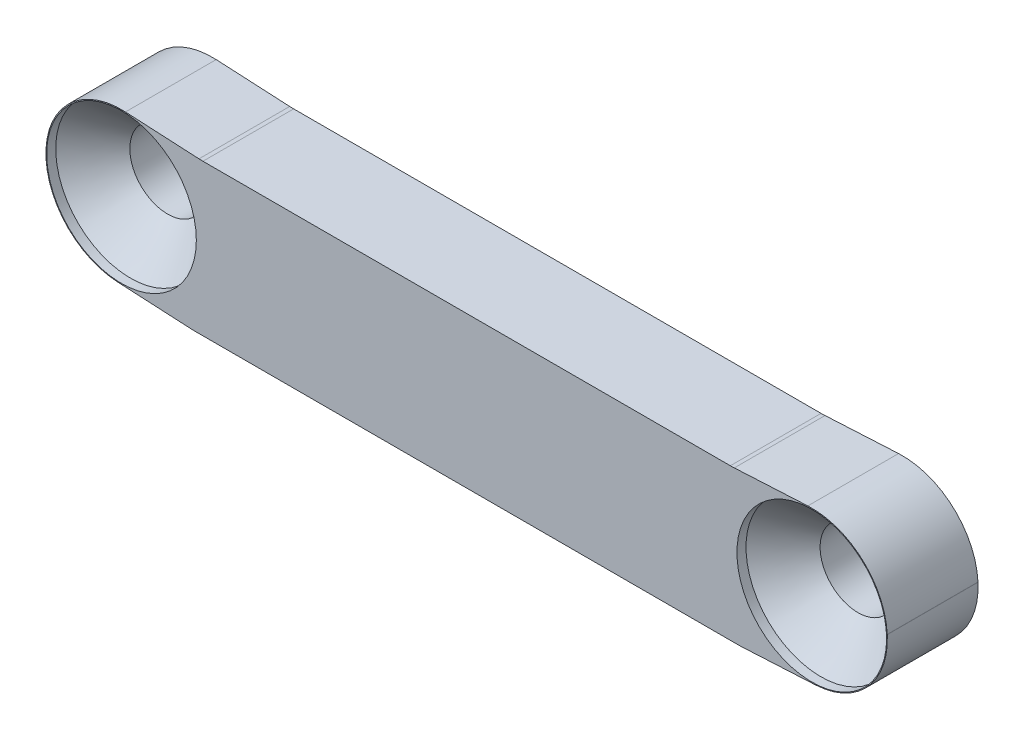
SolidWorks part; units mm, degrees
ref_plane "Front Plane" through (0, 0, 0) normal (0, 0, 1) x (1, 0, 0)
ref_plane "Top Plane" through (0, 0, 0) normal (0, 1, 0) x (1, 0, 0)
ref_plane "Right Plane" through (0, 0, 0) normal (1, 0, 0) x (0, 0, -1)
sketch "Sketch1" plane through (0, 0, 0) normal (0, 0, 1) x (1, 0, 0)
  line L0 (-9.0478, -24.5601) -> (9.0478, -24.5601)
  line L1 (-13.7926, -19.5601) -> (13.7926, -19.5601)
  line L2 (-8.7857, -19.5601) -> (-13.7789, -19.2985)
  line L3 (0, 3.2292) -> (0, -2.4346) construction
  line L4 (8.7857, -19.5601) -> (13.7789, -19.2985)
  line L6 (12, 4.3084) -> (12, 10.9702)
  line L7 (10.5, 12.4702) -> (4.0797, 12.4702)
  line L8 (2.5818, 11.0487) -> (2.4454, 8.4459)
  line L9 (7.7394, 0.4056) -> (9.0478, -24.5601)
  line L10 (9.0478, -24.5601) -> (14.0409, -24.2985)
  line L11 (14.0409, -24.2985) -> (12.7325, 0.6673)
  line L12 (12, 4.3084) -> (12, 10.9702)
  line L13 (10.5, 12.4702) -> (4.0797, 12.4702)
  line L14 (2.5818, 11.0487) -> (2.4454, 8.4459)
  line L15 (7.7394, 0.4056) -> (9.0478, -24.5601)
  line L16 (9.0478, -24.5601) -> (14.0409, -24.2985)
  line L17 (14.0409, -24.2985) -> (12.7325, 0.6673)
  line L18 (-4.0797, 12.4702) -> (-10.5, 12.4702)
  line L19 (-12, 10.9702) -> (-12, 4.3084)
  line L20 (-12.7325, 0.6673) -> (-14.0409, -24.2985)
  line L21 (-14.0409, -24.2985) -> (-9.0478, -24.5601)
  line L22 (-9.0478, -24.5601) -> (-7.7394, 0.4056)
  line L23 (-2.4454, 8.4459) -> (-2.5818, 11.0487)
  line L24 (-4.0797, 12.4702) -> (-10.5, 12.4702)
  line L25 (-12, 10.9702) -> (-12, 4.3084)
  line L26 (-12.7325, 0.6673) -> (-14.0409, -24.2985)
  line L27 (-14.0409, -24.2985) -> (-9.0478, -24.5601)
  line L28 (-9.0478, -24.5601) -> (-7.7394, 0.4056)
  line L29 (-2.4454, 8.4459) -> (-2.5818, 11.0487)
  circle A0 centre (11.4135, -21.9327) radius 1.5 construction
  circle A1 centre (-11.4135, -21.9327) radius 1.5 construction
  circle A2 centre (11.4135, -21.9327) radius 1.5
  circle A3 centre (-11.4135, -21.9327) radius 1.5
  circle A4 centre (-11.4135, -21.9327) radius 1.25
  arc A5 (12, 10.9702) -> (10.5, 12.4702) centre (10.5, 10.9702) ccw
  arc A6 (4.0797, 12.4702) -> (2.5818, 11.0487) centre (4.0797, 10.9702) ccw
  arc A7 (2.4454, 8.4459) -> (3.3039, 7.0105) centre (3.9433, 8.3674) ccw
  arc A8 (7.7394, 0.4056) -> (3.3039, 7.0105) centre (0, 0) ccw
  arc A9 (12.7325, 0.6673) -> (12, 4.3084) centre (0, 0) ccw
  arc A10 (12, 10.9702) -> (10.5, 12.4702) centre (10.5, 10.9702) ccw
  arc A11 (4.0797, 12.4702) -> (2.5818, 11.0487) centre (4.0797, 10.9702) ccw
  arc A12 (2.4454, 8.4459) -> (3.3039, 7.0105) centre (3.9433, 8.3674) ccw
  arc A13 (7.7394, 0.4056) -> (3.3039, 7.0105) centre (0, 0) ccw
  arc A14 (12.7325, 0.6673) -> (12, 4.3084) centre (0, 0) ccw
  arc A15 (-10.5, 12.4702) -> (-12, 10.9702) centre (-10.5, 10.9702) ccw
  arc A16 (-12, 4.3084) -> (-12.7325, 0.6673) centre (0, 0) ccw
  arc A17 (-3.3039, 7.0105) -> (-7.7394, 0.4056) centre (0, 0) ccw
  arc A18 (-3.3039, 7.0105) -> (-2.4454, 8.4459) centre (-3.9433, 8.3674) ccw
  arc A19 (-2.5818, 11.0487) -> (-4.0797, 12.4702) centre (-4.0797, 10.9702) ccw
  arc A20 (-10.5, 12.4702) -> (-12, 10.9702) centre (-10.5, 10.9702) ccw
  arc A21 (-12, 4.3084) -> (-12.7325, 0.6673) centre (0, 0) ccw
  arc A22 (-3.3039, 7.0105) -> (-7.7394, 0.4056) centre (0, 0) ccw
  arc A23 (-3.3039, 7.0105) -> (-2.4454, 8.4459) centre (-3.9433, 8.3674) ccw
  arc A24 (-2.5818, 11.0487) -> (-4.0797, 12.4702) centre (-4.0797, 10.9702) ccw
  circle A25 centre (11.4135, -21.9327) radius 1.25
  dimension "D4" = 2.5
  dimension "D3" = 5
  dimension "D1" = 0
  dimension "D2" = 0
extrude "Boss-Extrude1" add sketch "Sketch1" along normal blind 3 contours L28 L0 L15 L1 | L27 L28 L1 L26 A3 | L16 L17 L1 L15 A2 | A3 A4 | A2 A25 | L2 L26 L1 | L1 L17 L4 | L1 L3 L0 L15
fillet "Fillet1" radius 2.5 8 edges at (-8.7857, -19.5601, 1.5) (8.7857, -19.5601, 1.5) (9.0478, -24.5601, 1.5) (-9.0478, -24.5601, 1.5) (-13.7789, -19.2985, 1.5) (-14.0409, -24.2985, 1.5) (13.7789, -19.2985, 1.5) (14.0409, -24.2985, 1.5)
hole_wizard "CSK for M2.5 Flat Head Machine Screw2" positions "Sketch4" profile "Sketch5" countersink size "M2.5" standard "ANSI Metric"
sketch "Sketch4" plane through (0, 0, 3) normal (0, 0, 1) x (1, 0, 0)
  point P0 (-11.4135, -21.9327)
  point P3 (11.4135, -21.9327)
sketch "Sketch5" plane through (-11.4135, -21.9327, 3) normal (1, 0, 0) x (0, -1, 0)
  line L0 (0, 0) -> (0, 5.7511)
  line L1 (0, 5.7511) -> (1.25, 5)
  line L2 (1.25, 5) -> (1.25, 1.525)
  line L3 (1.25, 1.525) -> (2.475, 0.3)
  line L4 (2.475, 0.3) -> (2.475, 0)
  line L6 (2.475, 0) -> (0, 0)
  line L7 (-1.25, 1.525) -> (-2.475, 0.3) construction
  line L10 (0, 5.7511) -> (-1.25, 5) construction
  line L11 (0, -6.35) -> (0, 107.95) construction
  dimension "Hole Dia." = 2.5
  dimension "Hole Depth" = 5
  dimension "C'Sink Dia." = 4.95
  dimension "C'Sink Angle" = 90
  dimension "Drill Angle" = 118
  dimension "Head Clearance" = 0.3
